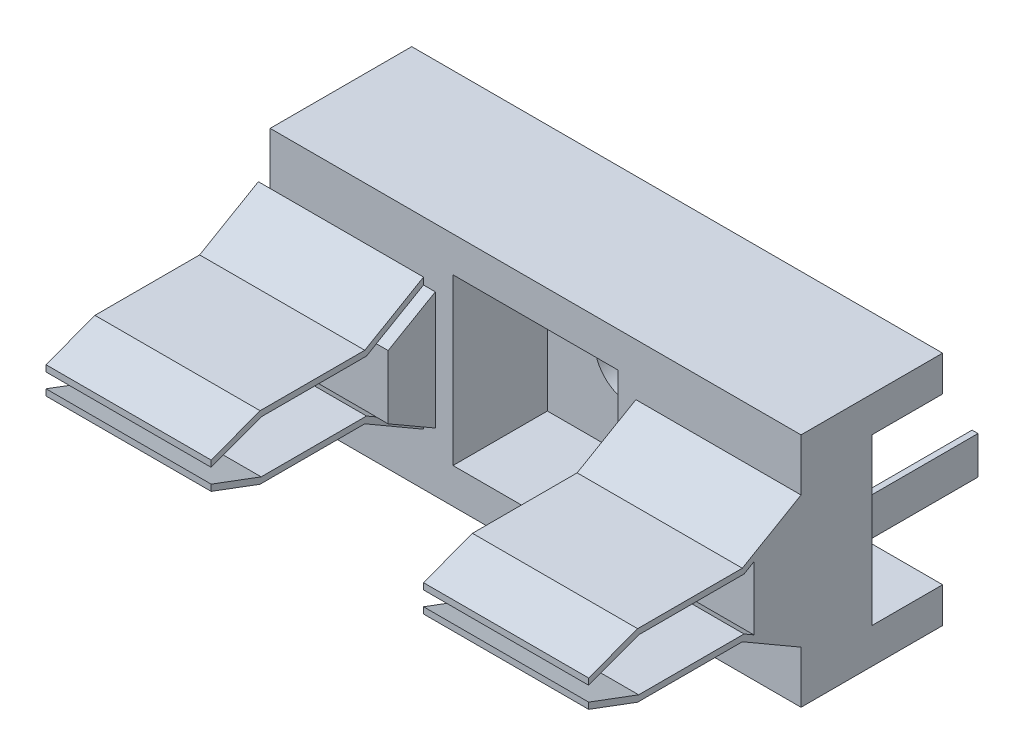
SolidWorks part; units mm, degrees
ref_plane "前视基准面" through (0, 0, 0) normal (0, 0, 1) x (1, 0, 0)
ref_plane "上视基准面" through (0, 0, 0) normal (0, 1, 0) x (1, 0, 0)
ref_plane "右视基准面" through (0, 0, 0) normal (1, 0, 0) x (0, 0, -1)
sketch "草图1" plane through (0, 0, 0) normal (0, 0, 1) x (1, 0, 0)
  line L0 (0, 0) -> (22.5, 0)
  line L1 (22.5, 0) -> (22.5, 10)
  line L2 (22.5, 10) -> (0, 10)
  line L3 (0, 10) -> (0, 0)
  dimension "D1" = 22.5
  dimension "D2" = 10
extrude "凸台-拉伸1" add sketch "草图1" along normal blind 6
sketch "草图2" plane through (0, 0, 0) normal (0, 0, -1) x (-1, 0, 0)
  line L0 (-11.25, 10) -> (-11.25, 0) construction
  line L1 (-22.5, 10) -> (0, 10) construction
  line L2 (0, 0) -> (-22.5, 0) construction
  line L3 (-22.5, 5) -> (0, 5) construction
  line L4 (-22.5, 0) -> (-22.5, 10) construction
  line L5 (0, 10) -> (0, 0) construction
  circle A0 centre (-11.25, 5) radius 1.5
  dimension "D1" = 3
extrude "切除-拉伸1" cut sketch "草图2" against normal through all
sketch "草图3" plane through (0, 0, 0) normal (0, 0, -1) x (-1, 0, 0)
  line L0 (-16.75, 8.5) -> (-16.75, 1.5)
  line L1 (-11.25, 0) -> (-11.25, 10) construction
  line L2 (0, 0) -> (-22.5, 0) construction
  line L3 (-22.5, 10) -> (0, 10) construction
  line L4 (-22.5, 8.5) -> (-16.75, 8.5)
  line L5 (-22.5, 0) -> (-22.5, 10) construction
  line L6 (-22.5, 5) -> (0, 5) construction
  line L7 (0, 10) -> (0, 0) construction
  line L8 (-22.5, 1.5) -> (-16.75, 1.5)
  line L9 (-22.5, 8.5) -> (-22.5, 1.5)
  line L10 (0, 1.5) -> (-5.75, 1.5)
  line L11 (-5.75, 8.5) -> (-5.75, 1.5)
  line L12 (0, 8.5) -> (0, 1.5)
  line L13 (0, 8.5) -> (-5.75, 8.5)
  dimension "D1" = 11
  dimension "D2" = 1.5
extrude "切除-拉伸2" cut sketch "草图3" against normal blind 3
sketch "草图4" plane through (0, 0, 6) normal (0, 0, 1) x (1, 0, 0)
  line L0 (-989, 5) -> (49011, 5) construction
  line L1 (11.25, -995) -> (11.25, 49005) construction
  line L2 (14.75, 1.5) -> (14.75, 8.5)
  line L3 (14.75, 1.5) -> (11.25, 1.5)
  line L4 (7.75, 1.5) -> (7.75, 8.5)
  line L5 (7.75, 1.5) -> (11.25, 1.5)
  line L7 (7.75, 8.5) -> (11.25, 8.5)
  line L8 (14.75, 8.5) -> (11.25, 8.5)
  point P13 (7.75, 5)
  point P14 (14.75, 5)
  dimension "D1" = 7
  dimension "D2" = 3.5
extrude "切除-拉伸3" cut sketch "草图4" against normal blind 4
sketch "草图5" plane through (0, 0, 6) normal (0, 0, 1) x (1, 0, 0)
  line L0 (22.5, 5) -> (0, 5) construction
  line L1 (22.5, 0) -> (22.5, 10) construction
  line L2 (0, 10) -> (0, 0) construction
  line L3 (15.5, 7.5) -> (22.5, 7.5)
  line L5 (15.5, 7.5) -> (15.5, 2.5)
  line L6 (22.5, 7.5) -> (22.5, 2.5)
  line L7 (15.5, 2.5) -> (22.5, 2.5)
  line L8 (11.25, 8.5) -> (11.25, 1.5) construction
  line L9 (14.75, 8.5) -> (7.75, 8.5) construction
  line L10 (7.75, 1.5) -> (14.75, 1.5) construction
  line L11 (7, 2.5) -> (0, 2.5)
  line L12 (7, 7.5) -> (0, 7.5)
  line L13 (0, 7.5) -> (0, 2.5)
  line L14 (7, 7.5) -> (7, 2.5)
  point P10 (15.5, 5)
  dimension "D1" = 5
  dimension "D2" = 7
extrude "凸台-拉伸2" add sketch "草图5" along normal blind 2
sketch "草图6" plane through (22.5, 0, 0) normal (1, 0, 0) x (0, 0, -1)
  line L0 (-6, 7.5) -> (-8, 6.3453)
  line L1 (-8, 2.5) -> (-8, 7.5) construction
  line L2 (-8, 7.5) -> (-6, 7.5) construction
  line L3 (-8, 6.3453) -> (-8, 7.5)
  line L4 (-8, 7.5) -> (-6, 7.5)
  line L5 (-8, 5) -> (-5.6194, 5) construction
  line L6 (-8, 3.6547) -> (-8, 2.5)
  line L7 (-8, 2.5) -> (-6, 2.5)
  line L8 (-6, 2.5) -> (-8, 3.6547)
  dimension "D1" = 30
extrude "切除-拉伸4" cut sketch "草图6" against normal through all
sketch "草图7" plane through (22.5, 0, 0) normal (1, 0, 0) x (0, 0, -1)
  line L0 (-6, 7.5) -> (-8.1786, 6.2373)
  line L1 (-8.1786, 6.2373) -> (-8.4155, 6.1)
  line L2 (-8, 5) -> (-5.2084, 5) construction
  line L3 (-15, 5.5756) -> (-12.926, 6.35)
  line L4 (-6, 2.5) -> (-8.1786, 3.7627)
  line L5 (-8.1786, 3.7627) -> (-8.4155, 3.9)
  line L6 (-15, 4.6913) -> (-15, 4.4244)
  line L7 (-15, 5.3087) -> (-15, 5.5756)
  line L8 (-12.8809, 3.9) -> (-8.4155, 3.9)
  line L9 (-12.8809, 6.1) -> (-8.4155, 6.1)
  line L10 (-12.926, 3.65) -> (-8.4887, 3.65)
  line L11 (-12.926, 6.35) -> (-8.4887, 6.35)
  line L12 (-15, -9.5969) -> (-15, 21.5023) construction
  line L13 (-12.8809, 6.1) -> (-15, 5.3087)
  line L14 (-8.4887, 3.65) -> (-6.1579, 2.2991)
  line L15 (-15, 4.4244) -> (-12.926, 3.65)
  line L16 (-12.8809, 3.9) -> (-15, 4.6913)
  line L17 (-6, 7.5) -> (-6, 7.7924)
  line L19 (-8.4887, 6.35) -> (-6.1579, 7.7009)
  line L20 (-6.1579, 7.7009) -> (-6, 7.7924)
  line L21 (-6.1579, 2.2991) -> (-6, 2.2076)
  line L22 (-6, 0) -> (-6, 2.5) construction
  line L23 (-6, 2.2076) -> (-6, 2.5)
  dimension "D2" = 2.2
  dimension "D3" = 0.25
  dimension "D4" = 15
  dimension "D5" = 0.25
extrude "凸台-拉伸3" add sketch "草图7" against normal blind 7
ref_plane "基准面1" through (11, 0, 0) normal (1, 0, 0) x (0, 0, -1)
mirror "镜向1" about plane through (11, 0, 0) normal (1, 0, 0) of "凸台-拉伸3"
sketch "草图8" plane through (0, 0, 3) normal (0, 0, -1) x (-1, 0, 0)
  line L0 (-22.5, 5) -> (0, 5) construction
  line L1 (-22.5, 8.5) -> (-22.5, 1.5) construction
  line L2 (0, 1.5) -> (0, 8.5) construction
  line L3 (-0.25, 5.8) -> (0, 5.8)
  line L4 (0, 5.8) -> (0, 4.9926)
  line L5 (-0.25, 5.8) -> (-0.25, 4.2)
  line L6 (-0.25, 4.2) -> (0, 4.2)
  line L7 (0, 4.2) -> (0, 5.0074)
  point P13 (-0.25, 5)
  line M1 (0, 1.5) -> (0, 8.5)
  dimension "D1" = 0.25
  dimension "D2" = 0.8
extrude "凸台-拉伸4" add sketch "草图8" along normal blind 5 contours L5 L0 L7 L4 L3 | L0 L5 L6 M1
mirror "镜向2" about plane through (11, 0, 0) normal (1, 0, 0) of "凸台-拉伸4"
